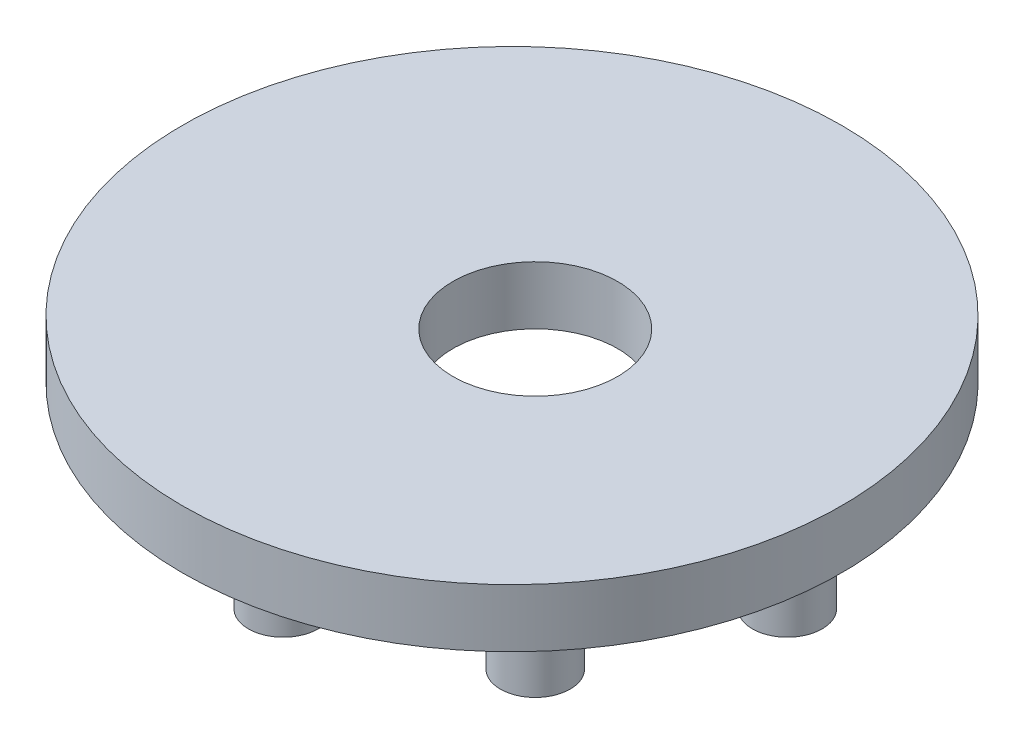
SolidWorks part; units mm, degrees
ref_plane "Front Plane" through (0, 0, 0) normal (0, 0, 1) x (1, 0, 0)
ref_plane "Top Plane" through (0, 0, 0) normal (0, 1, 0) x (1, 0, 0)
ref_plane "Right Plane" through (0, 0, 0) normal (1, 0, 0) x (0, 0, -1)
sketch "Sketch1" plane through (0, 0, 0) normal (0, 1, 0) x (1, 0, 0)
  circle A0 centre (1.2, 0) radius 13 construction
  circle A1 centre (-7.9924, 9.1924) radius 1.8
  circle A10 centre (1.2, 0) radius 4.25
  circle A11 centre (1.2, 0) radius 13 construction
  circle A12 centre (1.2, 13) radius 1.8
  circle A13 centre (10.3924, 9.1924) radius 1.8
  circle A14 centre (14.2, 0) radius 1.8
  circle A15 centre (10.3924, -9.1924) radius 1.8
  circle A16 centre (1.2, -13) radius 1.8
  circle A17 centre (-7.9924, -9.1924) radius 1.8
  circle A18 centre (-11.8, 0) radius 1.8
  circle A19 centre (0, 0) radius 17
  point P0 (1.2, -13)
  point P7 (0, 0)
  dimension "D1" = 26
  dimension "D2" = 3.6
  dimension "D4" = 1.2
  dimension "D5" = 8.5
  dimension "D7" = 26
  dimension "D6" = 34
  dimension "D3" = 8
extrude "Boss-Extrude2" add sketch "Sketch1" along normal blind 3
sketch "Sketch2" plane through (0, 3, 0) normal (0, 1, 0) x (1, 0, 0)
  circle A1 centre (-7.9924, 9.1924) radius 1.8
  circle A2 centre (-7.9924, 9.1924) radius 1.8 construction
extrude "Boss-Extrude4" add sketch "Sketch2" against normal offset from surface (6 mm away) 3 up to face at (0, 0, 17) offset beyond the face yes
pattern_circular "CirPattern1" count 8 over 360 about axis through (1.2, 0, 0) along (0, 1, 0) of "Boss-Extrude4"
sketch "Sketch6" plane through (0, 0, 0) normal (0, 1, 0) x (1, 0, 0)
  line L0 (-30.6051, 0) -> (34.7487, 0) construction
  line L1 (0, 0) -> (0, 29.2445) construction
  spline S0 degree 4 poles (11.6189, 16.5432) (11.8178, 16.5149) (12.2108, 16.4276) (12.9492, 16.1436) (13.746, 15.5555) (14.3617, 14.7904) (14.7236, 13.9501) (14.8612, 13.2918) (14.865, 12.6715) (14.8197, 12.1053) (14.83, 11.5815) (14.8956, 11.1092) (15.007, 10.6932) (15.1452, 10.3349) (15.3154, 10.0076) (15.511, 9.7126) (15.7246, 9.4508) (15.9525, 9.2201) (16.1975, 9.0122) (16.4653, 8.8248) (16.7029, 8.6844) (16.9312, 8.5703) (17.1246, 8.4809) (17.3959, 8.3693) (17.5318, 8.3168) (17.8356, 8.1923) (18.031, 8.0988) (18.2545, 7.9769) (18.4535, 7.8462) (18.6983, 7.6613) (18.9517, 7.427) (19.209, 7.1339) (19.4525, 6.7789) (19.6486, 6.416) (19.8087, 6.0265) (19.9293, 5.6134) (20.0053, 5.1807) (20.0322, 4.7331) (20.0052, 4.2575) (19.9105, 3.7618) (19.734, 3.2584) (19.4598, 2.7684) (19.1286, 2.3294) (18.8254, 1.8814) (18.5806, 1.4078) (18.4064, 0.9137) (18.2839, 0.2821) (18.2883, -0.4839) (18.4665, -1.1796) (18.761, -1.77) (19.0269, -2.1778) (19.2109, -2.4357) (19.3957, -2.6929) (19.5656, -2.9607) (19.7479, -3.3127) (19.9386, -3.8341) (20.0574, -4.5402) (20.0084, -5.4053) (19.7399, -6.2999) (19.3164, -7.0355) (18.8045, -7.5977) (18.2523, -8.0019) (17.7028, -8.2583) (17.046, -8.4959) (16.3381, -8.8646) (15.6539, -9.4505) (15.1112, -10.2886) (14.8757, -11.08) (14.8227, -11.7251) (14.8331, -12.2747) (14.8653, -12.7277) (14.8627, -13.2601) (14.7284, -13.933) (14.4312, -14.6359) (13.9398, -15.3293) (13.2393, -15.9473) (12.4754, -16.3531) (11.7867, -16.5408) (11.2352, -16.5867) (10.8405, -16.5694) (10.5271, -16.5278) (10.2173, -16.4674) (9.9074, -16.4068) (9.4278, -16.3326) (8.7706, -16.3058) (7.9522, -16.4462) (7.0575, -16.8866) (6.3973, -17.4923) (5.9486, -18.142) (5.6247, -18.753) (5.2858, -19.2492) (4.8047, -19.7257) (4.176, -20.14) (3.4024, -20.4398) (2.5087, -20.57) (1.6927, -20.5039) (0.9916, -20.296) (0.4189, -19.998) (-0.0273, -19.6575) (-0.4146, -19.2674) (-0.8145, -18.9035) (-1.248, -18.5935) (-1.7119, -18.3505) (-2.3194, -18.1387) (-3.0782, -18.0333) (-3.7924, -18.11) (-4.4191, -18.3171) (-4.861, -18.5221) (-5.1425, -18.6675) (-5.4235, -18.8139) (-5.7127, -18.9442) (-6.0871, -19.0749) (-6.6306, -19.1899) (-7.3467, -19.2073) (-8.1962, -19.036) (-9.0436, -18.6432) (-9.7116, -18.1198) (-10.1953, -17.5335) (-10.5171, -16.93) (-10.6931, -16.3498) (-10.8346, -15.6663) (-11.0981, -14.9129) (-11.5802, -14.1521) (-12.3327, -13.4935) (-13.154, -13.1159) (-13.9425, -12.956) (-14.6452, -12.9123) (-15.2508, -12.8226) (-15.8975, -12.5902) (-16.5474, -12.1958) (-17.16, -11.6117) (-17.6691, -10.8344) (-17.9616, -10.0228) (-18.0497, -9.3149) (-18.017, -8.7626) (-17.9441, -8.3745) (-17.8585, -8.0703) (-17.7548, -7.7723) (-17.6507, -7.4743) (-17.5088, -7.0104) (-17.3883, -6.3641) (-17.4099, -5.5341) (-17.7175, -4.5856) (-18.2225, -3.8453) (-18.8015, -3.308) (-19.3605, -2.9003) (-19.8039, -2.4944) (-20.2076, -1.9504) (-20.5288, -1.269) (-20.7158, -0.4605) (-20.7178, 0.4427) (-20.5366, 1.2408) (-20.2316, 1.9051) (-19.8556, 2.4296) (-19.4556, 2.8229) (-19.0146, 3.1507) (-18.5974, 3.4944) (-18.2288, 3.8789) (-17.9219, 4.3031) (-17.6253, 4.8739) (-17.4121, 5.6098) (-17.3857, 6.3278) (-17.501, 6.9779) (-17.6409, 7.4447) (-17.7447, 7.7443) (-17.8497, 8.0433) (-17.9378, 8.3482) (-18.0142, 8.7375) (-18.051, 9.292) (-17.9667, 10.0036) (-17.6765, 10.8204) (-17.1675, 11.6035) (-16.5546, 12.1903) (-15.906, 12.5859) (-15.2632, 12.8188) (-14.6642, 12.9109) (-13.9676, 12.9536) (-13.185, 13.1065) (-12.3627, 13.4746) (-11.6037, 14.1249) (-11.1111, 14.8837) (-10.8676, 15.5695) (-10.7424, 16.1072) (-10.6331, 16.5515) (-10.4857, 16.9859) (-10.2015, 17.5258) (-9.7176, 18.1133) (-9.0531, 18.6371) (-8.2109, 19.0306) (-7.3665, 19.205) (-6.6533, 19.1918) (-6.1116, 19.0813) (-5.7378, 18.9541) (-5.4489, 18.8264) (-5.1688, 18.6814) (-4.8888, 18.536) (-4.4501, 18.3294) (-3.8279, 18.1177) (-3.0036, 18.0202) (-2.0208, 18.1887) (-1.2156, 18.5825) (-0.6007, 19.0789) (-0.1174, 19.5743) (0.3474, 19.956) (0.9434, 20.2787) (1.6637, 20.5001) (2.4907, 20.5705) (3.385, 20.4443) (4.1492, 20.1518) (4.7633, 19.7558) (5.229, 19.3095) (5.5616, 18.8581) (5.8234, 18.3752) (6.1038, 17.9134) (6.4315, 17.4937) (6.8071, 17.1293) (7.2217, 16.8315) (7.6634, 16.6034) (8.1203, 16.4444) (8.5815, 16.3511) (9.0507, 16.319) (9.4616, 16.3412) (9.8101, 16.3903) (10.0986, 16.4439) (10.3282, 16.4895) (10.5311, 16.526) (10.7049, 16.5505) (10.8484, 16.5653) (10.9716, 16.5733) (11.0921, 16.577) (11.1677, 16.5774) (11.2594, 16.5751) (11.3499, 16.5709) (11.4367, 16.5647) (11.5194, 16.5564) (11.6217, 16.5435) (11.7453, 16.524) (11.889, 16.4956) (12.0913, 16.4453) (12.3305, 16.3702) (12.602, 16.2618) (12.9005, 16.1114) (13.1849, 15.9359) (13.4773, 15.7195) (13.7698, 15.4569) (14.0541, 15.1433) (14.3167, 14.7752) (14.5534, 14.3454) (14.7409, 13.8521) (14.8591, 13.2967) (14.8673, 12.6928) (14.8104, 11.9996) (14.8464, 11.2056) (15.0918, 10.3263) (15.5701, 9.57) (16.1316, 9.0373) (16.5735, 8.7549) (16.8048, 8.6327) (16.9225, 8.5759) knots 0 0 0 0 0 0.005432 0.010864 0.021228 0.026411 0.031594 0.035438 0.039283 0.043127 0.046971 0.049563 0.052156 0.054748 0.057341 0.059524 0.061707 0.06389 0.066073 0.068256 0.070439 0.07153 0.072622 0.074805 0.076449 0.078093 0.079737 0.081382 0.083026 0.08467 0.087958 0.090741 0.093524 0.096307 0.09909 0.102115 0.105141 0.108166 0.111192 0.114971 0.11875 0.122529 0.126307 0.129839 0.133371 0.136903 0.140435 0.147176 0.153918 0.15606 0.158202 0.160344 0.162486 0.164628 0.16677 0.171054 0.177448 0.183843 0.189974 0.196106 0.20019 0.204275 0.20836 0.212445 0.219092 0.225739 0.23241 0.239081 0.24113 0.243178 0.247276 0.251373 0.255471 0.261622 0.267773 0.274148 0.280522 0.284792 0.286927 0.289062 0.291197 0.293332 0.295467 0.297602 0.304323 0.311044 0.317625 0.324205 0.32825 0.332295 0.33634 0.340384 0.346455 0.352526 0.358575 0.364624 0.368401 0.372178 0.375955 0.379732 0.383263 0.386793 0.390324 0.393854 0.400599 0.407343 0.409486 0.411628 0.413771 0.415914 0.418057 0.4202 0.424485 0.430883 0.43728 0.443409 0.449537 0.453621 0.457704 0.461787 0.465871 0.472515 0.479159 0.485846 0.492533 0.496656 0.50078 0.504903 0.509026 0.515118 0.52121 0.527582 0.533954 0.538222 0.540357 0.542491 0.544625 0.546759 0.548893 0.551027 0.557745 0.564464 0.571047 0.57763 0.581676 0.585723 0.589769 0.593816 0.59989 0.605963 0.612009 0.618055 0.621831 0.625606 0.629382 0.633157 0.636687 0.640216 0.643745 0.647274 0.654021 0.660768 0.662911 0.665055 0.667199 0.669342 0.671486 0.67363 0.677917 0.684317 0.690717 0.696843 0.702969 0.707051 0.711133 0.715214 0.719296 0.725937 0.732578 0.739268 0.745958 0.750083 0.752145 0.754208 0.758333 0.762458 0.768552 0.774647 0.781016 0.787386 0.791652 0.793786 0.795919 0.798052 0.800186 0.802319 0.804452 0.811168 0.817883 0.824469 0.831054 0.835103 0.839151 0.843199 0.847248 0.853324 0.8594 0.865444 0.871487 0.875261 0.879035 0.882809 0.886583 0.89011 0.893638 0.897166 0.900694 0.903866 0.907039 0.910211 0.913384 0.916556 0.918143 0.919729 0.921315 0.922901 0.923694 0.924488 0.925281 0.926074 0.926638 0.927203 0.927767 0.928331 0.928896 0.92946 0.930589 0.931717 0.932846 0.935103 0.937361 0.939618 0.941875 0.944133 0.947186 0.95024 0.953293 0.956347 0.960414 0.964482 0.968549 0.972617 0.979237 0.985858 0.992929 0.996465 1 1 1 1 1 construction
  spline S1 degree 4 poles (18.3, 0) (18.3, -0.215) (18.3388, -0.6792) (18.4818, -1.2103) (18.761, -1.77) (19.0269, -2.1778) (19.2109, -2.4357) (19.3957, -2.6929) (19.5656, -2.9607) (19.7479, -3.3127) (19.9386, -3.8341) (20.0574, -4.5402) (20.0084, -5.4053) (19.7399, -6.2999) (19.3164, -7.0355) (18.8045, -7.5977) (18.2523, -8.0019) (17.7028, -8.2583) (17.046, -8.4959) (16.3381, -8.8646) (15.6539, -9.4505) (15.1112, -10.2886) (14.8757, -11.08) (14.8227, -11.7251) (14.8331, -12.2747) (14.8653, -12.7277) (14.8627, -13.2601) (14.7284, -13.933) (14.4312, -14.6359) (13.9398, -15.3293) (13.2393, -15.9473) (12.4754, -16.3531) (11.7867, -16.5408) (11.2352, -16.5867) (10.8405, -16.5694) (10.5271, -16.5278) (10.2173, -16.4674) (9.9074, -16.4068) (9.4278, -16.3326) (8.7706, -16.3058) (7.9522, -16.4462) (7.0575, -16.8866) (6.3973, -17.4923) (5.9486, -18.142) (5.6247, -18.753) (5.2858, -19.2492) (4.8047, -19.7257) (4.176, -20.14) (3.4024, -20.4398) (2.5087, -20.57) (1.6927, -20.5039) (0.9916, -20.296) (0.4189, -19.998) (-0.0273, -19.6575) (-0.4146, -19.2674) (-0.8145, -18.9035) (-1.248, -18.5935) (-1.7119, -18.3505) (-2.3194, -18.1387) (-3.0782, -18.0333) (-3.7924, -18.11) (-4.4191, -18.3171) (-4.861, -18.5221) (-5.1425, -18.6675) (-5.4235, -18.8139) (-5.7127, -18.9442) (-6.0871, -19.0749) (-6.6306, -19.1899) (-7.3467, -19.2073) (-8.1962, -19.036) (-9.0436, -18.6432) (-9.7116, -18.1198) (-10.1953, -17.5335) (-10.5171, -16.93) (-10.6931, -16.3498) (-10.8346, -15.6663) (-11.0981, -14.9129) (-11.5802, -14.1521) (-12.3327, -13.4935) (-13.154, -13.1159) (-13.9425, -12.956) (-14.6452, -12.9123) (-15.2508, -12.8226) (-15.8975, -12.5902) (-16.5474, -12.1958) (-17.16, -11.6117) (-17.6691, -10.8344) (-17.9616, -10.0228) (-18.0497, -9.3149) (-18.017, -8.7626) (-17.9441, -8.3745) (-17.8585, -8.0703) (-17.7548, -7.7723) (-17.6507, -7.4743) (-17.5088, -7.0104) (-17.3883, -6.3641) (-17.4099, -5.5341) (-17.7175, -4.5856) (-18.2225, -3.8453) (-18.8015, -3.308) (-19.3605, -2.9003) (-19.8039, -2.4944) (-20.2076, -1.9504) (-20.5295, -1.2674) (-20.6657, -0.677) (-20.7, -0.2262) (-20.7, 0) knots 0.14136 0.14136 0.14136 0.14136 0.14136 0.147176 0.153918 0.15606 0.158202 0.160344 0.162486 0.164628 0.16677 0.171054 0.177448 0.183843 0.189974 0.196106 0.20019 0.204275 0.20836 0.212445 0.219092 0.225739 0.23241 0.239081 0.24113 0.243178 0.247276 0.251373 0.255471 0.261622 0.267773 0.274148 0.280522 0.284792 0.286927 0.289062 0.291197 0.293332 0.295467 0.297602 0.304323 0.311044 0.317625 0.324205 0.32825 0.332295 0.33634 0.340384 0.346455 0.352526 0.358575 0.364624 0.368401 0.372178 0.375955 0.379732 0.383263 0.386793 0.390324 0.393854 0.400599 0.407343 0.409486 0.411628 0.413771 0.415914 0.418057 0.4202 0.424485 0.430883 0.43728 0.443409 0.449537 0.453621 0.457704 0.461787 0.465871 0.472515 0.479159 0.485846 0.492533 0.496656 0.50078 0.504903 0.509026 0.515118 0.52121 0.527582 0.533954 0.538222 0.540357 0.542491 0.544625 0.546759 0.548893 0.551027 0.557745 0.564464 0.571047 0.57763 0.581676 0.585723 0.589769 0.593816 0.59989 0.60601 0.60601 0.60601 0.60601 0.60601
  spline S2 degree 4 poles (18.3, 0) (18.3, 0.215) (18.3388, 0.6792) (18.4818, 1.2103) (18.761, 1.77) (19.0269, 2.1778) (19.2109, 2.4357) (19.3957, 2.6929) (19.5656, 2.9607) (19.7479, 3.3127) (19.9386, 3.8341) (20.0574, 4.5402) (20.0084, 5.4053) (19.7399, 6.2999) (19.3164, 7.0355) (18.8045, 7.5977) (18.2523, 8.0019) (17.7028, 8.2583) (17.046, 8.4959) (16.3381, 8.8646) (15.6539, 9.4505) (15.1112, 10.2886) (14.8757, 11.08) (14.8227, 11.7251) (14.8331, 12.2747) (14.8653, 12.7277) (14.8627, 13.2601) (14.7284, 13.933) (14.4312, 14.6359) (13.9398, 15.3293) (13.2393, 15.9473) (12.4754, 16.3531) (11.7867, 16.5408) (11.2352, 16.5867) (10.8405, 16.5694) (10.5271, 16.5278) (10.2173, 16.4674) (9.9074, 16.4068) (9.4278, 16.3326) (8.7706, 16.3058) (7.9522, 16.4462) (7.0575, 16.8866) (6.3973, 17.4923) (5.9486, 18.142) (5.6247, 18.753) (5.2858, 19.2492) (4.8047, 19.7257) (4.176, 20.14) (3.4024, 20.4398) (2.5087, 20.57) (1.6927, 20.5039) (0.9916, 20.296) (0.4189, 19.998) (-0.0273, 19.6575) (-0.4146, 19.2674) (-0.8145, 18.9035) (-1.248, 18.5935) (-1.7119, 18.3505) (-2.3194, 18.1387) (-3.0782, 18.0333) (-3.7924, 18.11) (-4.4191, 18.3171) (-4.861, 18.5221) (-5.1425, 18.6675) (-5.4235, 18.8139) (-5.7127, 18.9442) (-6.0871, 19.0749) (-6.6306, 19.1899) (-7.3467, 19.2073) (-8.1962, 19.036) (-9.0436, 18.6432) (-9.7116, 18.1198) (-10.1953, 17.5335) (-10.5171, 16.93) (-10.6931, 16.3498) (-10.8346, 15.6663) (-11.0981, 14.9129) (-11.5802, 14.1521) (-12.3327, 13.4935) (-13.154, 13.1159) (-13.9425, 12.956) (-14.6452, 12.9123) (-15.2508, 12.8226) (-15.8975, 12.5902) (-16.5474, 12.1958) (-17.16, 11.6117) (-17.6691, 10.8344) (-17.9616, 10.0228) (-18.0497, 9.3149) (-18.017, 8.7626) (-17.9441, 8.3745) (-17.8585, 8.0703) (-17.7548, 7.7723) (-17.6507, 7.4743) (-17.5088, 7.0104) (-17.3883, 6.3641) (-17.4099, 5.5341) (-17.7175, 4.5856) (-18.2225, 3.8453) (-18.8015, 3.308) (-19.3605, 2.9003) (-19.8039, 2.4944) (-20.2076, 1.9504) (-20.5295, 1.2674) (-20.6657, 0.677) (-20.7, 0.2262) (-20.7, 0) knots 0.14136 0.14136 0.14136 0.14136 0.14136 0.147176 0.153918 0.15606 0.158202 0.160344 0.162486 0.164628 0.16677 0.171054 0.177448 0.183843 0.189974 0.196106 0.20019 0.204275 0.20836 0.212445 0.219092 0.225739 0.23241 0.239081 0.24113 0.243178 0.247276 0.251373 0.255471 0.261622 0.267773 0.274148 0.280522 0.284792 0.286927 0.289062 0.291197 0.293332 0.295467 0.297602 0.304323 0.311044 0.317625 0.324205 0.32825 0.332295 0.33634 0.340384 0.346455 0.352526 0.358575 0.364624 0.368401 0.372178 0.375955 0.379732 0.383263 0.386793 0.390324 0.393854 0.400599 0.407343 0.409486 0.411628 0.413771 0.415914 0.418057 0.4202 0.424485 0.430883 0.43728 0.443409 0.449537 0.453621 0.457704 0.461787 0.465871 0.472515 0.479159 0.485846 0.492533 0.496656 0.50078 0.504903 0.509026 0.515118 0.52121 0.527582 0.533954 0.538222 0.540357 0.542491 0.544625 0.546759 0.548893 0.551027 0.557745 0.564464 0.571047 0.57763 0.581676 0.585723 0.589769 0.593816 0.59989 0.60601 0.60601 0.60601 0.60601 0.60601
